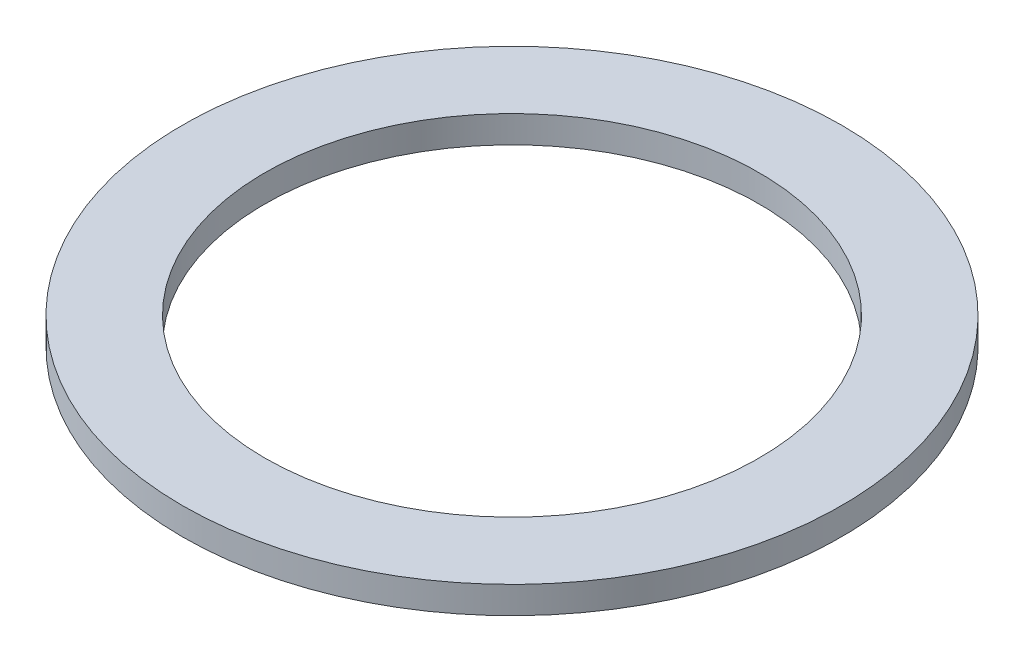
SolidWorks part; units mm, degrees
ref_plane "Front Plane" through (0, 0, 0) normal (0, 0, 1) x (1, 0, 0)
ref_plane "Top Plane" through (0, 0, 0) normal (0, 1, 0) x (1, 0, 0)
ref_plane "Right Plane" through (0, 0, 0) normal (1, 0, 0) x (0, 0, -1)
sketch "Sketch1" plane through (0, 0, 0) normal (0, 1, 0) x (1, 0, 0)
  circle A0 centre (0, 0) radius 19.304
  circle A1 centre (0, 0) radius 14.478
  dimension "D1" = 28.956
  dimension "D2" = 38.608
extrude "Boss-Extrude1" add sketch "Sketch1" along normal mid plane 1.5875
